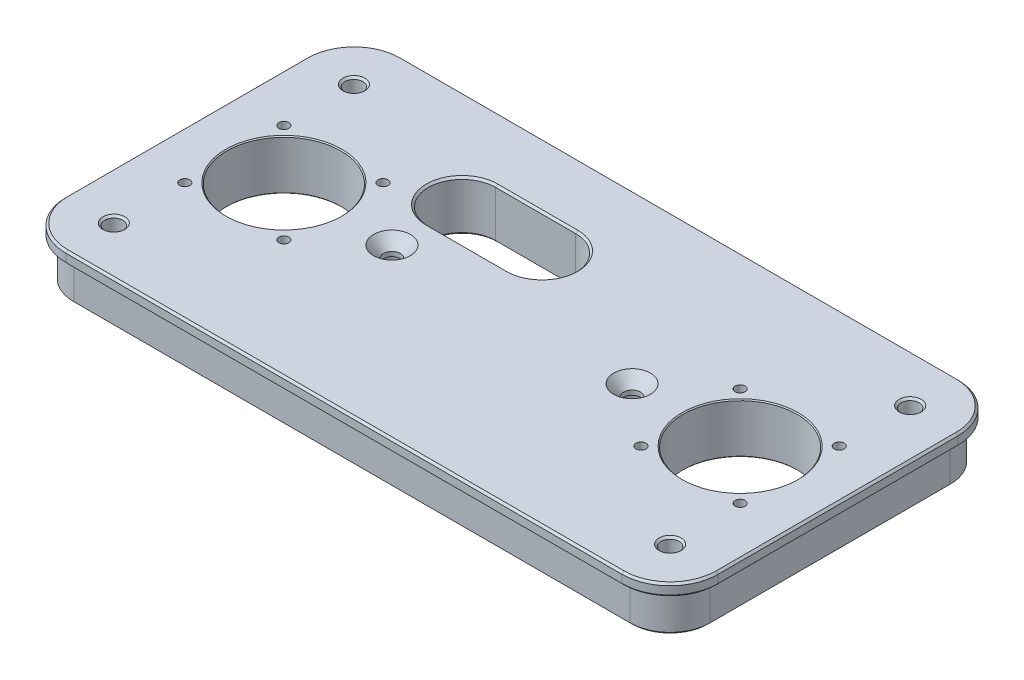
SolidWorks part; units mm, degrees
material "6061-T6 Aluminum"
ref_plane "Front Plane" through (0, 0, 0) normal (0, 0, 1) x (1, 0, 0)
ref_plane "Top Plane" through (0, 0, 0) normal (0, 1, 0) x (1, 0, 0)
ref_plane "Right Plane" through (0, 0, 0) normal (1, 0, 0) x (0, 0, -1)
sketch "Sketch1" plane through (0, 0, 0) normal (0, 1, 0) x (1, 0, 0)
  line L1 (-159, -80) -> (159, -80)
  line L2 (-159, -80) -> (-159, 80)
  line L3 (-159, 80) -> (159, 80)
  line L4 (159, -80) -> (159, 80)
  line L5 (-159, -80) -> (159, 80) construction
  line L6 (-159, 80) -> (159, -80) construction
  point P0 (0, 0)
  dimension "D1" = 160
  dimension "D2" = 318
extrude "Boss-Extrude1" add sketch "Sketch1" along normal blind 25
sketch "Sketch2" plane through (0, 25, 0) normal (0, 1, 0) x (1, 0, 0)
  line L0 (-114, 0) -> (0, 0) construction
  line L1 (0, 0) -> (114, 0) construction
  circle A0 centre (-114, 0) radius 28.5
  circle A1 centre (114, 0) radius 28.5
  dimension "D1" = 228
  dimension "D2" = 57
extrude "Cut-Extrude1" cut sketch "Sketch2" against normal through all
sketch "Sketch4" plane through (0, 25, 0) normal (0, 1, 0) x (1, 0, 0)
  line L0 (60, 0) -> (0, 0) construction
  line L1 (0, 0) -> (-60, 0) construction
  circle A0 centre (-60, 0) radius 9.55
  circle A1 centre (60, 0) radius 9.55
  dimension "D1" = 19.1
  dimension "D2" = 120
extrude "Cut-Extrude2" cut sketch "Sketch4" against normal through all both and the other way through all
chamfer "Chamfer1" distance 0.5 angle 45 8 edges at (114, 25, 28.5) (114, 0, 28.5) (60, 25, -9.55) (60, 0, 9.55) (-60, 25, -9.55) (-60, 0, 9.55) (-114, 25, 28.5) (-114, 0, 28.5)
fillet "Fillet1" radius 20 4 edges at (159, 12.5, 80) (159, 12.5, -80) (-159, 12.5, -80) (-159, 12.5, 80)
hole_wizard "M8 Clearance Hole1" positions "Sketch5" profile "Sketch6" hole size "M8" standard "ANSI Metric" end condition through all
sketch "Sketch5" plane through (0, 0, 0) normal (0, 1, 0) x (1, 0, 0)
  point P0 (-139, 60)
  point P3 (-139, -60)
  point P6 (139, 60)
  point P9 (139, -60)
sketch "Sketch6" plane through (-139, 0, -60) normal (1, 0, 0) x (0, 0, -1)
  line L0 (0, 0) -> (0, 25)
  line L1 (0, 25) -> (4.5, 25)
  line L2 (4.5, 25) -> (4.5, 0)
  line L5 (4.5, 0) -> (0, 0)
  line L11 (0, -6.35) -> (0, 107.95) construction
  dimension "Thru Hole Dia." = 9
  dimension "Thru Hole Depth" = 25
sketch "Sketch7" plane through (0, 0, 0) normal (0, -1, 0) x (1, 0, 0)
  line L1 (89.235, 24.765) -> (138.765, 24.765) construction
  line L2 (89.235, 24.765) -> (89.235, -24.765) construction
  line L3 (89.235, -24.765) -> (138.765, -24.765) construction
  line L4 (138.765, 24.765) -> (138.765, -24.765) construction
  line L5 (89.235, 24.765) -> (138.765, -24.765) construction
  line L6 (89.235, -24.765) -> (138.765, 24.765) construction
  line L7 (-138.765, 24.765) -> (-89.235, 24.765) construction
  line L8 (-138.765, 24.765) -> (-138.765, -24.765) construction
  line L9 (-138.765, -24.765) -> (-89.235, -24.765) construction
  line L10 (-89.235, 24.765) -> (-89.235, -24.765) construction
  line L11 (-138.765, 24.765) -> (-89.235, -24.765) construction
  line L12 (-138.765, -24.765) -> (-89.235, 24.765) construction
  circle A0 centre (89.235, 24.765) radius 3.302 construction
  circle A1 centre (138.765, -24.765) radius 3.302 construction
  circle A2 centre (138.765, 24.765) radius 3.302 construction
  circle A3 centre (89.235, -24.765) radius 3.302 construction
  circle A4 centre (89.235, 24.765) radius 3.302
  circle A5 centre (138.765, -24.765) radius 3.302
  circle A6 centre (138.765, 24.765) radius 3.302
  circle A7 centre (89.235, -24.765) radius 3.302
  circle A12 centre (-138.765, -24.765) radius 3.302
  circle A13 centre (-89.235, -24.765) radius 3.302
  circle A14 centre (-89.235, 24.765) radius 3.302
  circle A15 centre (-138.765, 24.765) radius 3.302
  point P13 (114, 0)
  point P15 (-114, 0)
hole_wizard "M6x1.0 Tapped Hole1" positions "Sketch8" profile "Sketch9" tap size "M6x1.0" standard "ANSI Metric" end condition through all
sketch "Sketch8" plane through (0, 0, 0) normal (0, -1, 0) x (-1, 0, 0)
  point P0 (138.765, -24.765)
  point P3 (89.235, -24.765)
  point P6 (89.235, 24.765)
  point P9 (138.765, 24.765)
  point P12 (-89.235, -24.765)
  point P15 (-138.765, -24.765)
  point P18 (-89.235, 24.765)
  point P21 (-138.765, 24.765)
cosmetic thread "Hole Thread11" parameters "D2"=6
cosmetic thread "Hole Thread12" parameters "D2"=6
cosmetic thread "Hole Thread13" parameters "D2"=6
cosmetic thread "Hole Thread14" parameters "D2"=6
cosmetic thread "Hole Thread16" parameters "D2"=6
sketch "Sketch9" plane through (-138.765, 0, 24.765) normal (1, 0, 0) x (0, 0, -1)
  line L0 (0, 0) -> (0, 25)
  line L1 (0, 25) -> (2.5, 25)
  line L2 (2.5, 25) -> (2.5, 0)
  line L5 (2.5, 0) -> (0, 0)
  line L11 (0, -6.35) -> (0, 107.95) construction
  dimension "Thru Tap Drill Dia." = 5
  dimension "Thru Tap Drill Depth" = 25
cosmetic thread "Hole Thread17" parameters "D2"=6
cosmetic thread "Hole Thread18" parameters "D2"=6
cosmetic thread "Hole Thread19" parameters "D2"=6
sketch "Sketch13" plane through (0, 25, 0) normal (0, 1, 0) x (1, 0, 0)
  circle A0 centre (60, 0) radius 13.411
  circle A1 centre (-60, 0) radius 14.7245
extrude "Boss-Extrude3" add sketch "Sketch13" against normal blind 8
hole_wizard "CSK for 5/16 Flat Head Socket Cap Screw1" positions "Sketch14" profile "Sketch15" countersink size "5/16" standard "ANSI Inch" end condition through all
sketch "Sketch14" plane through (0, 25, 0) normal (0, 1, 0) x (1, 0, 0)
  point P0 (60, 0)
  point P3 (-60, 0)
sketch "Sketch15" plane through (60, 25, 0) normal (1, 0, 0) x (0, 0, 1)
  line L0 (0, 0) -> (0, 25)
  line L1 (0, 25) -> (4.2164, 25)
  line L2 (4.2164, 25) -> (4.2164, 5.7335)
  line L3 (4.2164, 5.7335) -> (9.2005, 0)
  line L5 (9.2005, 0) -> (0, 0)
  line L6 (-4.2164, 5.7335) -> (-9.2005, 0) construction
  line L11 (0, -6.35) -> (0, 107.95) construction
  dimension "Thru Hole Dia." = 8.4328
  dimension "Thru Hole Depth" = 25
  dimension "Near C'Sink Dia." = 18.401
  dimension "Near C'Sink Angle" = 82
sketch "Sketch16" plane through (0, 25, 0) normal (0, -1, 0) x (1, 0, 0)
  line L4 (159, 60) -> (159, -60) construction
  line L5 (139, -80) -> (-139, -80) construction
  line L6 (-159, -60) -> (-159, 60) construction
  line L7 (-139, 80) -> (139, 80) construction
  line L8 (163, -60) -> (163, 60)
  line L9 (139, 84) -> (-139, 84)
  line L10 (-163, 60) -> (-163, -60)
  line L11 (-139, -84) -> (139, -84)
  line L12 (163, -60) -> (163, 60)
  line L13 (139, 84) -> (-139, 84)
  line L14 (-163, 60) -> (-163, -60)
  line L15 (-139, -84) -> (139, -84)
  line L16 (159, 60) -> (159, -60)
  line L17 (139, -80) -> (-139, -80)
  line L18 (-159, -60) -> (-159, 60)
  line L19 (-139, 80) -> (139, 80)
  arc A4 (159, 60) -> (139, 80) centre (139, 60) ccw construction
  arc A5 (139, -80) -> (159, -60) centre (139, -60) ccw construction
  arc A6 (-159, -60) -> (-139, -80) centre (-139, -60) ccw construction
  arc A7 (-139, 80) -> (-159, 60) centre (-139, 60) ccw construction
  arc A8 (163, 60) -> (139, 84) centre (139, 60) ccw
  arc A9 (-139, 84) -> (-163, 60) centre (-139, 60) ccw
  arc A10 (-163, -60) -> (-139, -84) centre (-139, -60) ccw
  arc A11 (139, -84) -> (163, -60) centre (139, -60) ccw
  arc A12 (163, 60) -> (139, 84) centre (139, 60) ccw
  arc A13 (-139, 84) -> (-163, 60) centre (-139, 60) ccw
  arc A14 (-163, -60) -> (-139, -84) centre (-139, -60) ccw
  arc A15 (139, -84) -> (163, -60) centre (139, -60) ccw
  arc A16 (159, 60) -> (139, 80) centre (139, 60) ccw
  arc A17 (139, -80) -> (159, -60) centre (139, -60) ccw
  arc A18 (-159, -60) -> (-139, -80) centre (-139, -60) ccw
  arc A19 (-139, 80) -> (-159, 60) centre (-139, 60) ccw
  dimension "D1" = 4
extrude "Boss-Extrude4" add sketch "Sketch16" along normal blind 6
sketch "Sketch17" plane through (0, 0, 0) normal (0, -1, 0) x (1, 0, 0)
  line L0 (-60, -35.0192) -> (-20, -35.0192) construction
  line L1 (-60, -18.1841) -> (-20, -18.1841)
  line L2 (-60, -51.8544) -> (-20, -51.8544)
  circle A0 centre (-60, -35.0192) radius 9.2363 construction
  arc A1 (-69.9426, -40.7596) -> (-50.0574, -40.7596) centre (-60, -35.0192) ccw construction
  arc A2 (-60, -18.1841) -> (-60, -51.8544) centre (-60, -35.0192) ccw
  arc A3 (-20, -51.8544) -> (-20, -18.1841) centre (-20, -35.0192) ccw
  point P2 (-40, -35.0192)
  dimension "D1" = 40
extrude "Cut-Extrude3" cut sketch "Sketch17" against normal through all
chamfer "Chamfer4" distance 1 angle 45 40 edges at (139, 0, -64.5) (139, 25, -64.5) (-139, 0, -64.5) (-139, 25, -64.5) (139, 0, 55.5) (139, 25, 55.5) (-139, 0, 55.5) (-139, 25, 55.5) (0, 19, -84) (155.9706, 19, -76.9706) (-155.9706, 19, -76.9706) (163, 19, 0) (-163, 19, 0) (155.9706, 19, 76.9706) (-155.9706, 19, 76.9706) (0, 19, 84) (0, 25, -84) (155.9706, 25, -76.9706) (-155.9706, 25, -76.9706) (163, 25, 0) (-163, 25, 0) (155.9706, 25, 76.9706) (-155.9706, 25, 76.9706) (0, 25, 84) (-40, 0, -18.1841) (-40, 25, -18.1841) (-76.8351, 0, -35.0192) (-76.8351, 25, -35.0192) (-3.1649, 0, -35.0192) (-3.1649, 25, -35.0192) (-40, 0, -51.8544) (-40, 25, -51.8544) (0, 0, -80) (-153.1421, 0, -74.1421) (153.1421, 0, -74.1421) (-159, 0, 0) (159, 0, 0) (-153.1421, 0, 74.1421) (153.1421, 0, 74.1421) (0, 0, 80)
sketch "Sketch18" plane through (0, 0, 0) normal (0, -1, 0) x (1, 0, 0)
  circle A8 centre (-105, -70) radius 3.25
  circle A9 centre (-75, -70) radius 3.25
  circle A10 centre (-45, -70) radius 3.25
  circle A11 centre (-15, -70) radius 3.25
  circle A12 centre (15, -70) radius 3.25
  circle A13 centre (45, -70) radius 3.25
  circle A14 centre (75, -70) radius 3.25
  circle A15 centre (105, -70) radius 3.25
  circle A24 centre (-105, 70) radius 3.25
  circle A25 centre (-75, 70) radius 3.25
  circle A26 centre (-45, 70) radius 3.25
  circle A27 centre (-15, 70) radius 3.25
  circle A28 centre (15, 70) radius 3.25
  circle A29 centre (45, 70) radius 3.25
  circle A30 centre (75, 70) radius 3.25
  circle A31 centre (105, 70) radius 3.25
hole_wizard "M6x1.0 Tapped Hole2" positions "Sketch19" profile "Sketch20" tap size "M6x1.0" standard "ANSI Metric"
sketch "Sketch19" plane through (0, 0, 0) normal (0, -1, 0) x (-1, 0, 0)
  point P1 (-75, 70)
  point P4 (-45, 70)
  point P7 (-105, 70)
  point P10 (-15, 70)
  point P13 (15, 70)
  point P16 (45, 70)
  point P19 (75, 70)
  point P22 (105, 70)
  point P25 (-105, -70)
  point P28 (-75, -70)
  point P31 (-45, -70)
  point P34 (-15, -70)
  point P37 (15, -70)
  point P40 (45, -70)
  point P43 (75, -70)
  point P46 (105, -70)
sketch "Sketch20" plane through (75, 0, -70) normal (1, 0, 0) x (0, 0, -1)
  line L0 (0, 0) -> (0, 16.5022)
  line L1 (0, 16.5022) -> (2.5, 15)
  line L2 (2.5, 15) -> (2.5, 0)
  line L5 (2.5, 0) -> (0, 0)
  line L10 (0, 16.5022) -> (-2.5, 15) construction
  line L11 (0, -6.35) -> (0, 107.95) construction
  dimension "Tap Drill Dia." = 5
  dimension "Tap Drill Depth" = 15
  dimension "Drill Angle" = 118
cosmetic thread "Hole Thread20" parameters "D1"=12, "D2"=6
cosmetic thread "Hole Thread21" parameters "D1"=12, "D2"=6
cosmetic thread "Hole Thread22" parameters "D1"=12, "D2"=6
cosmetic thread "Hole Thread23" parameters "D1"=12, "D2"=6
cosmetic thread "Hole Thread24" parameters "D1"=12, "D2"=6
cosmetic thread "Hole Thread25" parameters "D1"=12, "D2"=6
cosmetic thread "Hole Thread26" parameters "D1"=12, "D2"=6
cosmetic thread "Hole Thread27" parameters "D1"=12, "D2"=6
cosmetic thread "Hole Thread28" parameters "D1"=12, "D2"=6
cosmetic thread "Hole Thread29" parameters "D1"=12, "D2"=6
cosmetic thread "Hole Thread30" parameters "D1"=12, "D2"=6
cosmetic thread "Hole Thread31" parameters "D1"=12, "D2"=6
cosmetic thread "Hole Thread32" parameters "D1"=12, "D2"=6
cosmetic thread "Hole Thread33" parameters "D1"=12, "D2"=6
cosmetic thread "Hole Thread34" parameters "D1"=12, "D2"=6
cosmetic thread "Hole Thread35" parameters "D1"=12, "D2"=6
